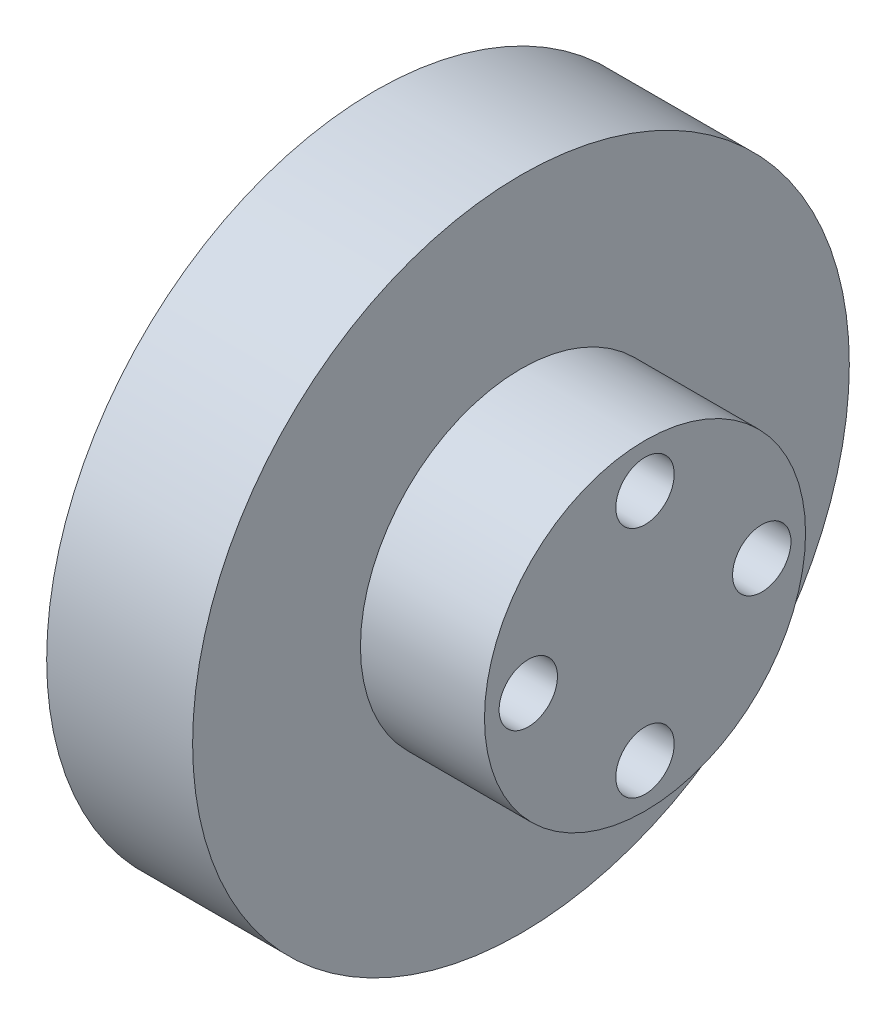
SolidWorks part; units mm, degrees
material "1060 Alloy"
ref_plane "Front Plane" through (0, 0, 0) normal (0, 0, 1) x (1, 0, 0)
ref_plane "Top Plane" through (0, 0, 0) normal (0, 1, 0) x (1, 0, 0)
ref_plane "Right Plane" through (0, 0, 0) normal (1, 0, 0) x (0, 0, -1)
sketch "Sketch3" plane through (0, 0, 0) normal (1, 0, 0) x (0, 0, -1)
  circle A0 centre (0, 0) radius 22.5
  dimension "D1" = 45
extrude "Boss-Extrude1" add sketch "Sketch3" along normal blind 10
sketch "Sketch4" plane through (10, 0, 0) normal (1, 0, 0) x (0, 0, -1)
  circle A0 centre (0, 0) radius 11
  dimension "D1" = 22
extrude "Boss-Extrude2" add sketch "Sketch4" along normal blind 8.5
sketch "Sketch5" plane through (18.5, 0, 0) normal (1, 0, 0) x (0, 0, -1)
  circle A0 centre (0, 8) radius 2
  circle A2 centre (8, 0) radius 2
  circle A3 centre (0, -8) radius 2
  circle A4 centre (-8, 0) radius 2
  dimension "D1" = 4
  dimension "D2" = 8
  dimension "D3" = 4
extrude "Cut-Extrude1" cut sketch "Sketch5" against normal through all
